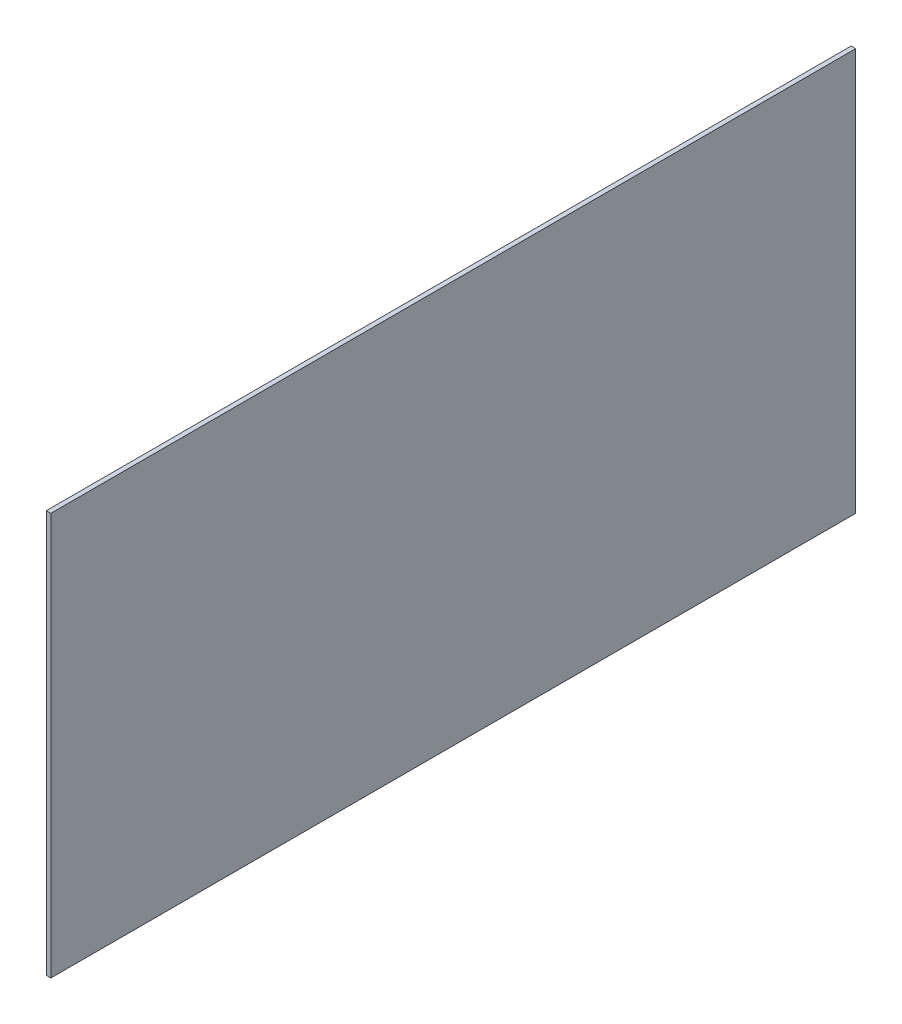
SolidWorks part; units mm, degrees
ref_plane "Front Plane" through (0, 0, 0) normal (0, 0, 1) x (1, 0, 0)
ref_plane "Top Plane" through (0, 0, 0) normal (0, 1, 0) x (1, 0, 0)
ref_plane "Right Plane" through (0, 0, 0) normal (1, 0, 0) x (0, 0, -1)
sketch "Sketch1" plane through (0, 0, 0) normal (1, 0, 0) x (0, 0, -1)
  line L1 (0, 0) -> (279.4, 0)
  line L2 (0, 0) -> (0, 139.7)
  line L3 (0, 139.7) -> (279.4, 139.7)
  line L4 (279.4, 0) -> (279.4, 139.7)
  dimension "D1" = 139.7
  dimension "D2" = 279.4
extrude "Boss-Extrude1" add sketch "Sketch1" along normal blind 1.5875
